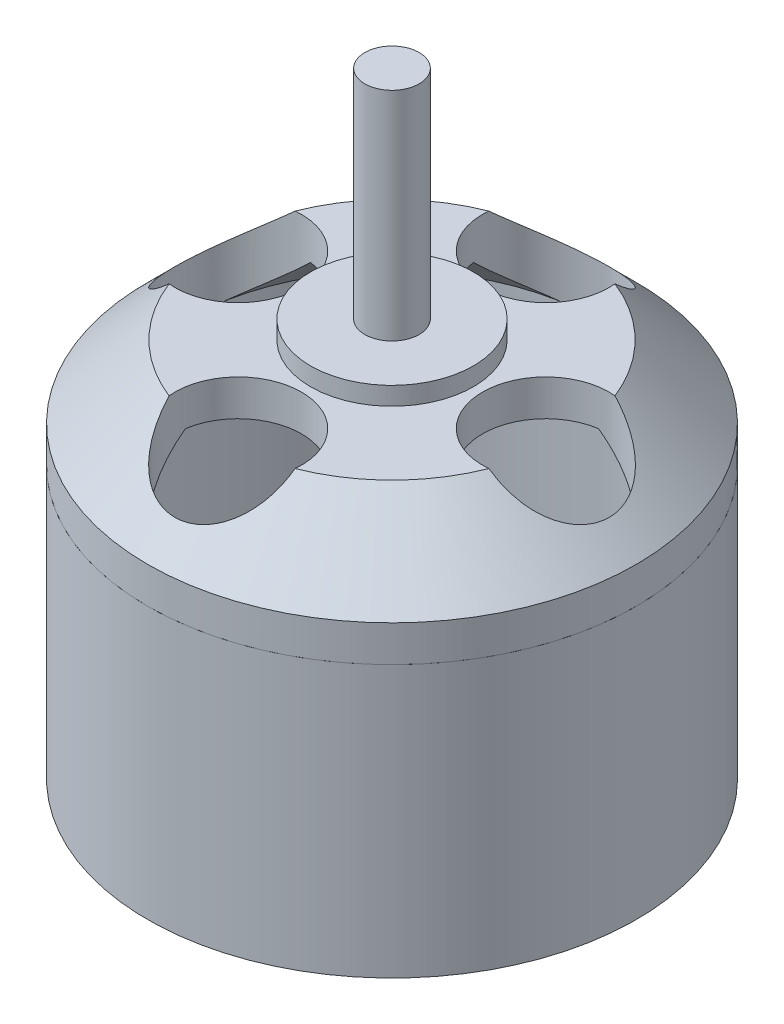
SolidWorks part; units mm, degrees
ref_plane "Ön Düzlem" through (0, 0, 0) normal (0, 0, 1) x (1, 0, 0)
ref_plane "Üst Düzlem" through (0, 0, 0) normal (0, 1, 0) x (1, 0, 0)
ref_plane "Sağ Düzlem" through (0, 0, 0) normal (1, 0, 0) x (0, 0, -1)
sketch "Çizim2" plane through (0, 0, 0) normal (0, 1, 0) x (1, 0, 0)
  circle A0 centre (0, 0) radius 13.5
  dimension "D1" = 27
extrude "Yükseklik-Ekstrüzyon1" add sketch "Çizim2" along normal blind 1
sketch "Çizim3" plane through (0, 1, 0) normal (0, 1, 0) x (1, 0, 0)
  circle A1 centre (0, 0) radius 13.5
  circle A2 centre (0, 0) radius 13.5
  dimension "D1" = 0
extrude "Yükseklik-Ekstrüzyon2" add sketch "Çizim3" along normal blind 5
chamfer "Pah1" distance 4 angle 45 1 edges at (0, 6, 13.5)
shell "İç Boşaltma1" thickness 2
sketch "Çizim5" plane through (0, 6, 0) normal (0, 1, 0) x (1, 0, 0)
  circle A0 centre (0, -8.5) radius 3.5
  circle A1 centre (-8.5, 0) radius 3.5
  circle A2 centre (0, 8.5) radius 3.5
  circle A3 centre (8.5, 0) radius 3.5
  point P12 (0, 0)
  dimension "D2" = 7
  dimension "D1" = 17
  dimension "D3" = 4
extrude "Kes-Ekstrüzyon1" cut sketch "Çizim5" against normal blind 6
sketch "Çizim6" plane through (0, 0, 0) normal (0, -1, 0) x (1, 0, 0)
  circle A2 centre (0, 0) radius 13.5 construction
  circle A3 centre (0, 0) radius 13.5
  circle A4 centre (0, 0) radius 12.5
  circle M9 centre (0, 0) radius 13.5
  dimension "D1" = 27
  dimension "D2" = 25
sketch "Çizim7" plane through (0, 6, 0) normal (0, 1, 0) x (1, 0, 0)
  circle A0 centre (0, 0) radius 4.5
  dimension "D1" = 9
extrude "Yükseklik-Ekstrüzyon4" add sketch "Çizim7" along normal blind 1
sketch "Çizim8" plane through (0, 7, 0) normal (0, 1, 0) x (1, 0, 0)
  circle A0 centre (0, 0) radius 1.5
  dimension "D1" = 3
extrude "Yükseklik-Ekstrüzyon6" add sketch "Çizim6" along normal blind 15 separate body contours A4 M9
extrude "Yükseklik-Ekstrüzyon7" add sketch "Çizim8" along normal blind 12 and the other way blind 27 separate body
